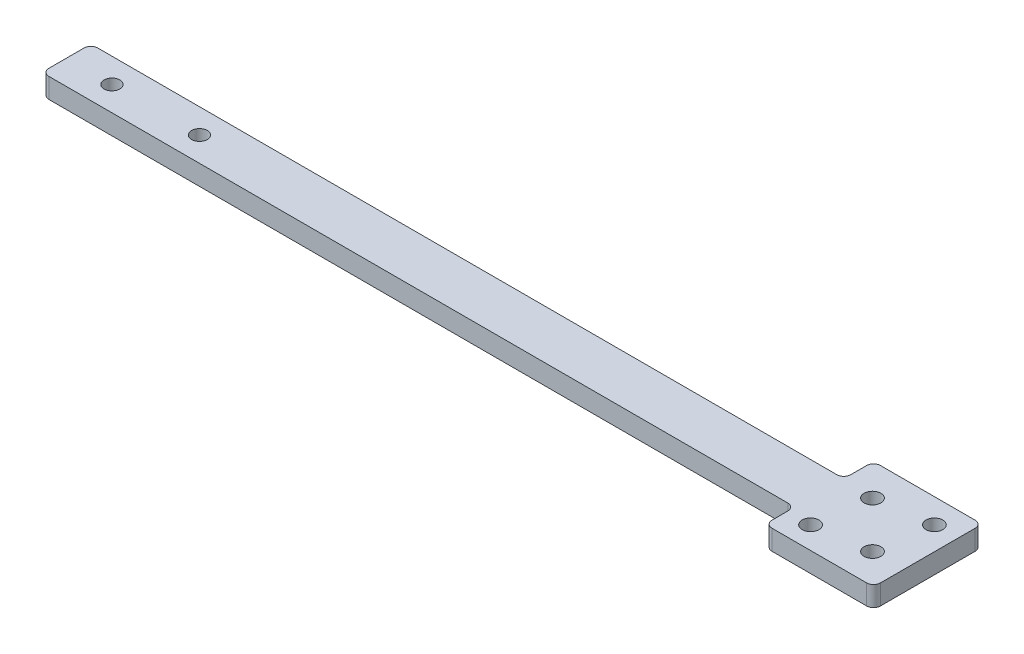
SolidWorks part; units mm, degrees
ref_plane "Front Plane" through (0, 0, 0) normal (0, 0, 1) x (1, 0, 0)
ref_plane "Top Plane" through (0, 0, 0) normal (0, 1, 0) x (1, 0, 0)
ref_plane "Right Plane" through (0, 0, 0) normal (1, 0, 0) x (0, 0, -1)
sketch "Sketch1" plane through (0, 0, 0) normal (0, 1, 0) x (1, 0, 0)
  line L1 (-164.4499, 7.3104) -> (50.5501, 7.3104)
  line L2 (-164.4499, 7.3104) -> (-164.4499, -6.6896)
  line L3 (-164.4499, -6.6896) -> (50.5501, -6.6896)
  line L4 (50.5501, 7.3104) -> (50.5501, -6.6896)
  dimension "D1" = 14
  dimension "D2" = 215
extrude "Boss-Extrude1" add sketch "Sketch1" along normal blind 5.715
sketch "Sketch2" plane through (0, 5.715, 0) normal (0, 1, 0) x (1, 0, 0)
  line L0 (-164.4499, 0.3104) -> (50.5501, 0.3104) construction
  line L1 (-164.4499, 7.3104) -> (-164.4499, -6.6896) construction
  line L2 (50.5501, -6.6896) -> (50.5501, 7.3104) construction
  circle A0 centre (-151.4499, 0.3104) radius 2.25
  circle A1 centre (-126.4499, 0.3104) radius 2.25
  dimension "D2" = 4.5
  dimension "D1" = 25
  dimension "D3" = 13
extrude "Cut-Extrude1" cut sketch "Sketch2" against normal through all
sketch "Sketch3" plane through (50.5501, 0, 0) normal (1, 0, 0) x (0, 0, -1)
  line L0 (-6.6896, 5.715) -> (7.3104, 5.715) construction
  line L1 (15.8104, 5.715) -> (-15.1896, 5.715)
  line L2 (15.8104, 5.715) -> (15.8104, 0)
  line L3 (15.8104, 0) -> (-15.1896, 0)
  line L4 (-15.1896, 5.715) -> (-15.1896, 0)
  line L5 (-6.6896, 0) -> (7.3104, 0) construction
  line L6 (0.3104, 5.715) -> (0.3104, 0) construction
  line L7 (-6.6896, 5.715) -> (-6.6896, 0) construction
  line L8 (7.3104, 5.715) -> (7.3104, 0) construction
  dimension "D1" = 31
extrude "Boss-Extrude2" add sketch "Sketch3" along normal blind 31
sketch "Sketch4" plane through (0, 5.715, 0) normal (0, 1, 0) x (1, 0, 0)
  line L0 (81.5501, 0) -> (-164.4499, 0) construction
  line L1 (81.5501, 15.8104) -> (81.5501, -15.1896) construction
  line L2 (66.0501, -15.1896) -> (66.0501, 15.8104) construction
  line L3 (81.5501, -15.1896) -> (50.5501, -15.1896) construction
  line L4 (81.5501, 15.8104) -> (50.5501, 15.8104) construction
  line L5 (59.4386, 6.6114) -> (66.0501, 0) construction
  line L6 (66.0501, 0) -> (74.8889, 8.8388) construction
  line L7 (-164.4499, 7.3104) -> (-164.4499, -6.6896) construction
  line L8 (66.0501, 0) -> (72.6615, -6.6114) construction
  line L9 (66.0501, 0) -> (57.2112, -8.8388) construction
  circle A0 centre (57.2112, -8.8388) radius 2.4
  circle A1 centre (59.4386, 6.6114) radius 2.4
  circle A2 centre (74.8889, 8.8388) radius 2.4
  circle A3 centre (72.6615, -6.6114) radius 2.4
  dimension "D1" = 4.8
  dimension "D2" = 25
  dimension "D3" = 45
  dimension "D4" = 18.7
extrude "Cut-Extrude2" cut sketch "Sketch4" against normal through all
fillet "Fillet1" radius 2 8 edges at (-164.4499, 2.8575, -7.3104) (-164.4499, 2.8575, 6.6896) (50.5501, 2.8575, -15.8104) (81.5501, 2.8575, -15.8104) (81.5501, 2.8575, 15.1896) (50.5501, 2.8575, 15.1896)
